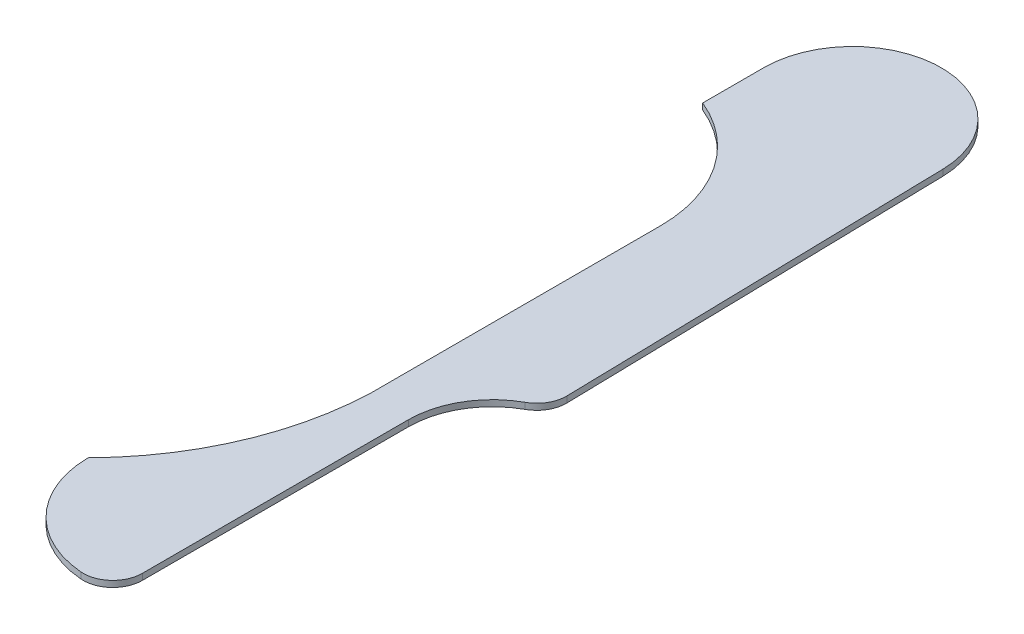
SolidWorks part; units mm, degrees
ref_plane "Płaszczyzna przednia" through (0, 0, 0) normal (0, 0, 1) x (1, 0, 0)
ref_plane "Płaszczyzna górna" through (0, 0, 0) normal (0, 1, 0) x (1, 0, 0)
ref_plane "Płaszczyzna prawa" through (0, 0, 0) normal (1, 0, 0) x (0, 0, -1)
sketch "Sketch1" plane through (0, 0, 0) normal (0, 1, 0) x (1, 0, 0)
  line L0 (0, -96.2847) -> (0, -45.5843) construction
  line L1 (8.9979, 2.4233) -> (9.8488, -36.5767)
  line L4 (-0.35, -44.1605) -> (-0.35, -16.9105)
  line L6 (-9, 2.227) -> (-9, -3.973)
  line L7 (3.9, -46.714) -> (3.9, -73.714)
  arc A0 (-9, 2.227) -> (8.9979, 2.4233) centre (0, 2.227) cw
  arc A1 (9.8488, -36.5767) -> (8.2975, -39.2696) centre (6.8496, -36.6421) cw
  arc A2 (8.2975, -39.2696) -> (3.9, -46.714) centre (12.4, -46.714) ccw
  arc A5 (-0.35, -16.9105) -> (-9, -3.973) centre (-14.35, -16.9105) ccw
  arc A7 (3.9, -73.714) -> (0.6601, -76.7044) centre (0.9, -73.714) cw
  arc A9 (0.6601, -76.7044) -> (-9, -66.3092) centre (1.4998, -66.238) cw
  arc A10 (-0.35, -44.1605) -> (-9, -66.3092) centre (-30.3315, -45.2149) cw
  point P15 (-9, -66.238)
  point P22 (0, 0)
  point P23 (-7.6728, -64.3604)
  point P24 (-7.6861, -66.4623)
  point P25 (0, 0)
  point P26 (-9, -66.238)
  dimension "D1" = 9
  dimension "D3" = 3
  dimension "D4" = 8.5
  dimension "D5" = 3.9
  dimension "D6" = 3
  dimension "D7" = 10.5
  dimension "D8" = 30
  dimension "D10" = 14
  dimension "D14" = 27
  dimension "D2" = 39
  dimension "D9" = 27.25
  dimension "D11" = 6.2
  dimension "D12" = 0.7
  dimension "D13" = 1.25
extrude "Boss-Extrude1" add sketch "Sketch1" along normal blind 0.625
